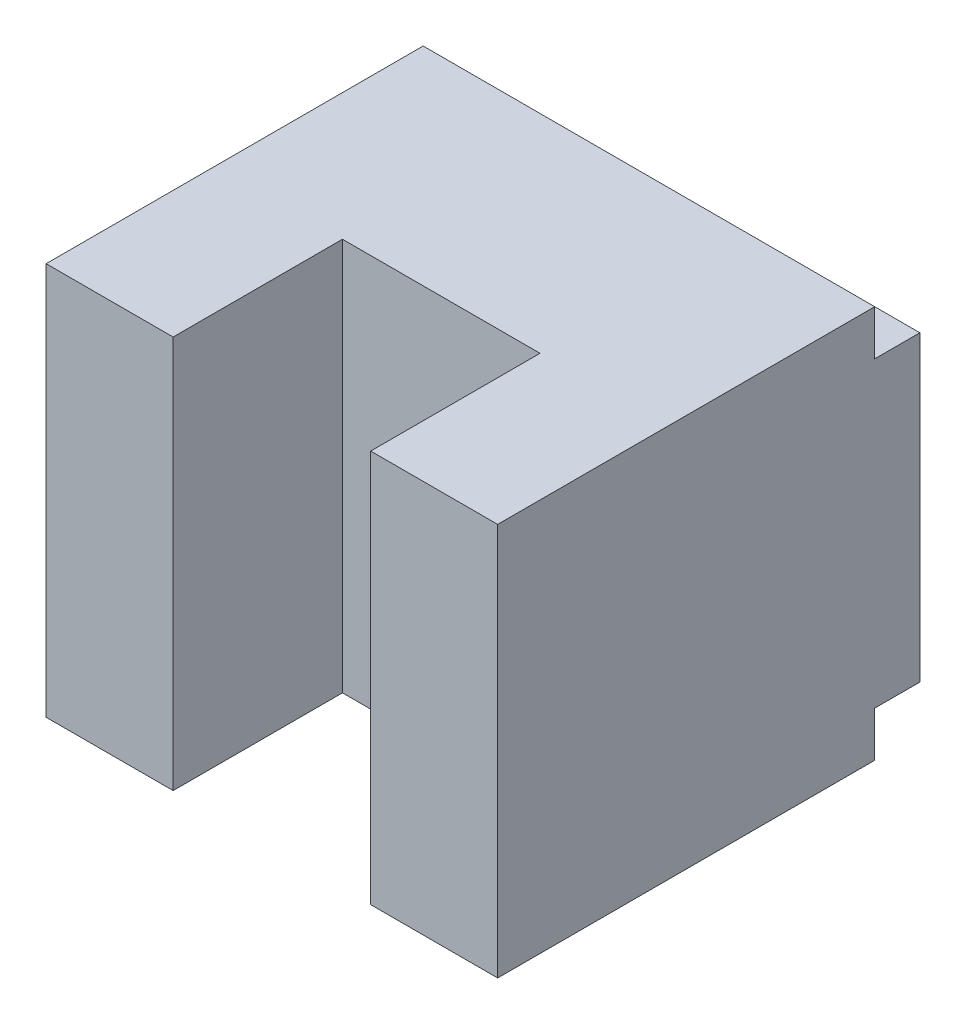
SolidWorks part; units mm, degrees
material "AISI 304"
ref_plane "Front Plane" through (0, 0, 0) normal (0, 0, 1) x (1, 0, 0)
ref_plane "Top Plane" through (0, 0, 0) normal (0, 1, 0) x (1, 0, 0)
ref_plane "Right Plane" through (0, 0, 0) normal (1, 0, 0) x (0, 0, -1)
sketch "Sketch1" plane through (0, 0, 0) normal (0, 0, 1) x (1, 0, 0)
  line L1 (-12.7, -11.049) -> (12.7, -11.049)
  line L2 (-12.7, -11.049) -> (-12.7, 11.049)
  line L3 (-12.7, 11.049) -> (12.7, 11.049)
  line L4 (12.7, -11.049) -> (12.7, 11.049)
  line L5 (-12.7, -11.049) -> (12.7, 11.049) construction
  line L6 (-12.7, 11.049) -> (12.7, -11.049) construction
  circle A0 centre (0, 0) radius 3.175
  point P0 (0, 0)
  dimension "D3" = 6.35
  dimension "D1" = 25.4
  dimension "D2" = 22.098
extrude "Boss-Extrude1" add sketch "Sketch1" along normal blind 23.749
sketch "Sketch2" plane through (0, 0, 23.749) normal (0, 0, 1) x (1, 0, 0)
  line L0 (12.7, 11.049) -> (-12.7, 11.049) construction
  line L1 (-5.5562, -11.049) -> (5.5563, -11.049)
  line L2 (-5.5562, -11.049) -> (-5.5562, 11.049)
  line L3 (-5.5562, 11.049) -> (5.5563, 11.049)
  line L4 (5.5563, -11.049) -> (5.5563, 11.049)
  line L5 (-5.5562, -11.049) -> (5.5563, 11.049) construction
  line L6 (-5.5562, 11.049) -> (5.5563, -11.049) construction
  point P0 (0, 0)
  dimension "D1" = 11.1125
extrude "Cut-Extrude1" cut sketch "Sketch2" against normal blind 9.525
sketch "Sketch3" plane through (0, 0, 0) normal (1, 0, 0) x (0, 0, -1)
  line L1 (0, 11.049) -> (-2.54, 11.049)
  line L2 (0, 11.049) -> (0, 8.509)
  line L3 (0, 8.509) -> (-2.54, 8.509)
  line L4 (-2.54, 11.049) -> (-2.54, 8.509)
  line L5 (0, -11.049) -> (-2.54, -11.049)
  line L6 (0, -11.049) -> (0, -8.509)
  line L7 (0, -8.509) -> (-2.54, -8.509)
  line L8 (-2.54, -11.049) -> (-2.54, -8.509)
  dimension "D1" = 2.54
  dimension "D2" = 2.54
  dimension "D3" = 2.54
  dimension "D4" = 2.54
extrude "Cut-Extrude2" cut sketch "Sketch3" against normal through all both and the other way through all
